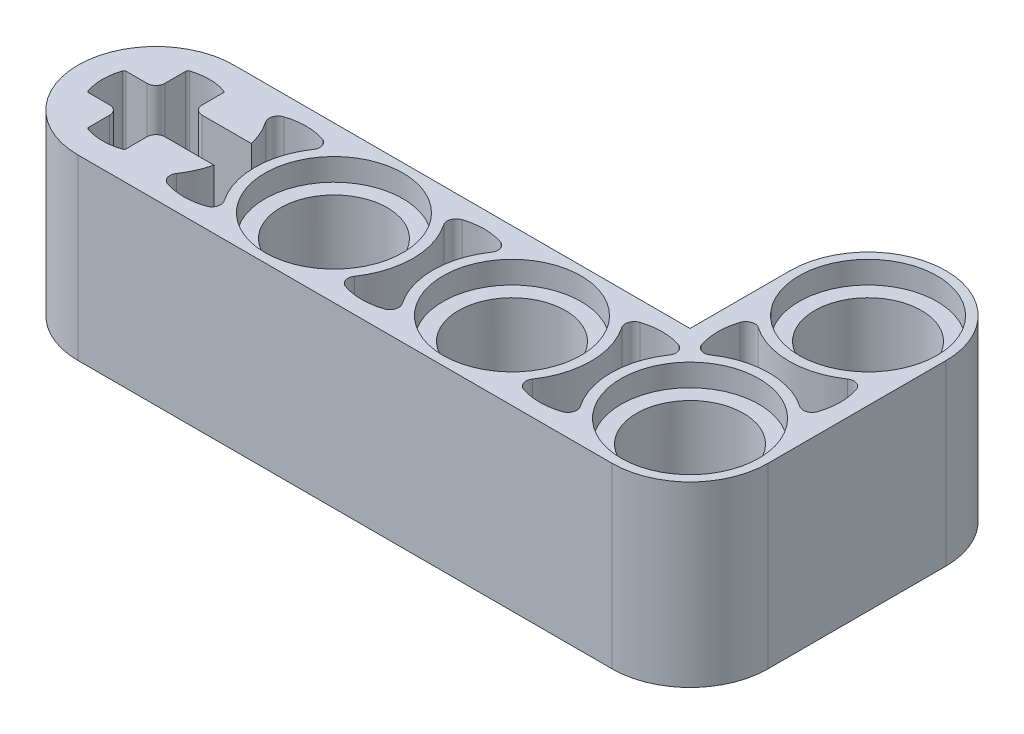
SolidWorks part; units mm, degrees
ref_plane "Front Plane" through (0, 0, 0) normal (0, 0, 1) x (1, 0, 0)
ref_plane "Top Plane" through (0, 0, 0) normal (0, 1, 0) x (1, 0, 0)
ref_plane "Right Plane" through (0, 0, 0) normal (1, 0, 0) x (0, 0, -1)
sketch "Sketch1" plane through (0, 0, 0) normal (0, 1, 0) x (1, 0, 0)
  line L5 (-15.5, -3.5) -> (15.5, -3.5)
  line L6 (-15.5, -3.5) -> (-15.5, 3.5)
  line L11 (-15.5, 3.5) -> (8.5, 3.5)
  line L12 (15.5, -3.5) -> (15.5, 3.5)
  line L13 (-15.5, -3.5) -> (15.5, 3.5) construction
  line L14 (-15.5, 3.5) -> (15.5, -3.5) construction
  line L16 (15.5, 3.5) -> (15.5, 11.5)
  line L17 (15.5, 11.5) -> (8.5, 11.5)
  line L18 (8.5, 3.5) -> (8.5, 11.5)
  point P0 (0, 0)
  dimension "D1" = 31
  dimension "D2" = 7
  dimension "D3" = 7
  dimension "D4" = 8
  dimension "D5" = 24
extrude "Boss-Extrude1" add sketch "Sketch1" along normal blind 8 contours L11 L18 L17 L16 L12 L5 L6
sketch "Sketch3" plane through (0, 8, 0) normal (0, 1, 0) x (1, 0, 0)
  line L0 (-12, 0) -> (-15.5, 0) construction
  line L1 (-15.5, -3.5) -> (-15.5, 3.5) construction
  line L2 (-12, 3.5) -> (-15.5, 3.5)
  line L3 (-15.5, 3.5) -> (-15.5, -3.5)
  line L4 (-15.5, -3.5) -> (-12, -3.5)
  line L5 (12, 0) -> (15.5, 0) construction
  line L6 (15.5, -3.5) -> (15.5, 11.5) construction
  line L7 (12, 0) -> (12, -3.5) construction
  line L8 (15.5, 0) -> (15.5, -3.5)
  line L9 (15.5, -3.5) -> (12, -3.5)
  line L10 (8.5, 3.5) -> (8.5, 11.5) construction
  line L11 (12, 8) -> (12, 11.5) construction
  line L12 (15.5, 11.5) -> (8.5, 11.5) construction
  line L13 (8.5, 8) -> (8.5, 11.5)
  line L14 (8.5, 11.5) -> (15.5, 11.5)
  line L15 (15.5, 11.5) -> (15.5, 8)
  arc A0 (-12, 3.5) -> (-12, -3.5) centre (-12, 0) ccw
  arc A1 (12, -3.5) -> (15.5, 0) centre (12, 0) ccw
  arc A3 (8.5, 8) -> (15.5, 8) centre (12, 8) cw
  line M5 (-15.5, 3.5) -> (-15.5, -3.5)
  line M6 (-15.5, -3.5) -> (15.5, -3.5)
  line M7 (15.5, -3.5) -> (15.5, 11.5)
  line M8 (15.5, 11.5) -> (8.5, 11.5)
  line M9 (8.5, 11.5) -> (8.5, 3.5)
  line M10 (8.5, 3.5) -> (-15.5, 3.5)
  dimension "D1" = 7
  dimension "D6" = 3.5
  dimension "D7" = 3.5
  dimension "D8" = 3.5
  dimension "D2" = 3.5
  dimension "D3" = 3.5
  dimension "D4" = 7
  dimension "D5" = 3.5
extrude "Cut-Extrude1" cut sketch "Sketch3" against normal blind 8 contours A0 M10 M5 | A0 L3 M6 | A1 M6 M7 | A3 M8 M7 | A3 L14 M9
sketch "Sketch8" plane through (0, 8, 0) normal (0, 1, 0) x (1, 0, 0)
  circle A0 centre (12, 8) radius 2.4
  circle A1 centre (12, 0) radius 2.4
  circle A2 centre (4, 0) radius 2.4
  circle A3 centre (-4, 0) radius 2.4
  dimension "D1" = 4.8
  dimension "D4" = 8
  dimension "D5" = 8
  dimension "D2" = 2
  dimension "D3" = 3
extrude "Cut-Extrude4" cut sketch "Sketch8" against normal through all
sketch "Sketch9" plane through (0, 8, 0) normal (0, 1, 0) x (1, 0, 0)
  circle A0 centre (12, 8) radius 3.1
  circle A1 centre (12, 0) radius 3.1
  circle A2 centre (4, 0) radius 3.1
  circle A3 centre (-4, 0) radius 3.1
  dimension "D1" = 6.2
  dimension "D4" = 8
  dimension "D5" = 8
  dimension "D2" = 2
  dimension "D3" = 3
extrude "Cut-Extrude5" cut sketch "Sketch9" against normal blind 1
ref_plane "Plane1" through (0, 4, 0) normal (0, 1, 0) x (1, 0, 0)
mirror "Mirror1" about plane through (0, 4, 0) normal (0, 1, 0) of "Cut-Extrude5"
sketch "Sketch10" plane through (0, 8, 0) normal (0, 1, 0) x (1, 0, 0)
  line L0 (12, 8) -> (12, 0) construction
  arc A0 (9.3899, 4.866) -> (9.3899, 3.134) centre (12, 4) ccw
  arc A1 (9.9954, 2.9299) -> (14.0046, 2.9299) centre (12, 0) cw
  arc A2 (9.9954, 5.0701) -> (14.0046, 5.0701) centre (12, 8) ccw
  arc A3 (14.6101, 3.134) -> (14.6101, 4.866) centre (12, 4) ccw
  arc A4 (14.0046, 2.9299) -> (14.6101, 3.134) centre (14.2304, 3.26) ccw
  arc A5 (14.0046, 5.0701) -> (14.6101, 4.866) centre (14.2304, 4.74) cw
  arc A6 (9.9954, 5.0701) -> (9.3899, 4.866) centre (9.7696, 4.74) ccw
  arc A7 (9.9954, 2.9299) -> (9.3899, 3.134) centre (9.7696, 3.26) cw
  arc A8 (7.134, -2.6101) -> (8.866, -2.6101) centre (8, 0) ccw
  arc A9 (9.0701, -2.0046) -> (8.866, -2.6101) centre (8.74, -2.2304) cw
  arc A10 (6.9299, -2.0046) -> (7.134, -2.6101) centre (7.26, -2.2304) ccw
  arc A11 (9.0701, -2.0046) -> (9.0701, 2.0046) centre (12, 0) cw
  arc A12 (9.0701, 2.0046) -> (8.866, 2.6101) centre (8.74, 2.2304) ccw
  arc A13 (8.866, 2.6101) -> (7.134, 2.6101) centre (8, 0) ccw
  arc A14 (6.9299, 2.0046) -> (7.134, 2.6101) centre (7.26, 2.2304) cw
  arc A15 (6.9299, -2.0046) -> (6.9299, 2.0046) centre (4, 0) ccw
  arc A16 (-0.866, -2.6101) -> (0.866, -2.6101) centre (0, 0) ccw
  arc A17 (1.0701, -2.0046) -> (0.866, -2.6101) centre (0.74, -2.2304) cw
  arc A18 (1.0701, -2.0046) -> (1.0701, 2.0046) centre (4, 0) cw
  arc A19 (1.0701, 2.0046) -> (0.866, 2.6101) centre (0.74, 2.2304) ccw
  arc A20 (0.866, 2.6101) -> (-0.866, 2.6101) centre (0, 0) ccw
  arc A21 (-1.0701, 2.0046) -> (-0.866, 2.6101) centre (-0.74, 2.2304) cw
  arc A22 (-1.0701, -2.0046) -> (-1.0701, 2.0046) centre (-4, 0) ccw
  arc A23 (-1.0701, -2.0046) -> (-0.866, -2.6101) centre (-0.74, -2.2304) ccw
  arc A24 (-8.866, -2.6101) -> (-7.134, -2.6101) centre (-8, 0) ccw
  arc A25 (-6.9299, -2.0046) -> (-7.134, -2.6101) centre (-7.26, -2.2304) cw
  arc A26 (-6.9299, -2.0046) -> (-6.9299, 2.0046) centre (-4, 0) cw
  arc A27 (-6.9299, 2.0046) -> (-7.134, 2.6101) centre (-7.26, 2.2304) ccw
  arc A28 (-7.134, 2.6101) -> (-8.866, 2.6101) centre (-8, 0) ccw
  arc A29 (-9.0701, 2.0046) -> (-8.866, 2.6101) centre (-8.74, 2.2304) cw
  arc A30 (-9.0701, -2.0046) -> (-9.0701, 2.0046) centre (-12, 0) ccw
  arc A31 (-9.0701, -2.0046) -> (-8.866, -2.6101) centre (-8.74, -2.2304) ccw
  point P11 (14.3844, 2.63)
  dimension "D1" = 3.55
  dimension "D2" = 3.55
  dimension "D3" = 2.75
  dimension "D4" = 0.4
  dimension "D7" = 8
  dimension "D8" = 5.6569
  dimension "D6" = 3
  dimension "D5" = 2
extrude "Cut-Extrude6" cut sketch "Sketch10" against normal through all
sketch "Sketch11" plane through (0, 8, 0) normal (0, 1, 0) x (1, 0, 0)
  line L0 (-13.24, 0.84) -> (-14.1777, 0.84)
  line L2 (-12.84, -2.1777) -> (-12.84, -1.24)
  line L4 (-11.16, -2.1777) -> (-11.16, -1.24)
  line L5 (-12.84, -2.2482) -> (-11.16, 2.2482) construction
  line L6 (-12.84, 2.2482) -> (-11.16, -2.2482) construction
  line L7 (-9.8223, 0.84) -> (-10.76, 0.84)
  line L9 (-9.8223, -0.84) -> (-10.76, -0.84)
  line L11 (-9.7518, 0.84) -> (-14.2482, -0.84) construction
  line L12 (-9.7518, -0.84) -> (-14.2482, 0.84) construction
  line L13 (-12.84, 1.24) -> (-12.84, 2.1777)
  line L14 (-11.16, 1.24) -> (-11.16, 2.1777)
  line L15 (-13.24, -0.84) -> (-14.1777, -0.84)
  line L16 (-9.7518, 0.84) -> (-8.5508, 0.84)
  line L17 (-9.7518, -0.84) -> (-8.5508, -0.84)
  line L18 (-9.8223, -0.84) -> (-9.7518, -0.84)
  line L19 (-9.8223, 0.84) -> (-9.7518, 0.84)
  arc A0 (-9.7276, -0.7722) -> (-9.7276, 0.7722) centre (-12, 0) ccw construction
  arc A1 (-11.2278, 2.2724) -> (-12.7722, 2.2724) centre (-12, 0) ccw
  arc A2 (-14.2724, 0.7722) -> (-14.2724, -0.7722) centre (-12, 0) ccw
  arc A3 (-12.7722, -2.2724) -> (-11.2278, -2.2724) centre (-12, 0) ccw
  arc A4 (-12.84, -1.24) -> (-13.24, -0.84) centre (-13.24, -1.24) ccw
  arc A5 (-11.16, -1.24) -> (-10.76, -0.84) centre (-10.76, -1.24) cw
  arc A6 (-10.76, 0.84) -> (-11.16, 1.24) centre (-10.76, 1.24) cw
  arc A7 (-13.24, 0.84) -> (-12.84, 1.24) centre (-13.24, 1.24) ccw
  arc A8 (-14.1777, 0.84) -> (-14.2724, 0.7722) centre (-14.1777, 0.74) ccw
  arc A9 (-14.1777, -0.84) -> (-14.2724, -0.7722) centre (-14.1777, -0.74) cw
  arc A10 (-12.7722, -2.2724) -> (-12.84, -2.1777) centre (-12.74, -2.1777) cw
  arc A11 (-11.2278, -2.2724) -> (-11.16, -2.1777) centre (-11.26, -2.1777) ccw
  arc A12 (-9.7276, -0.7722) -> (-9.8223, -0.84) centre (-9.8223, -0.74) cw construction
  arc A13 (-9.8223, 0.84) -> (-9.7276, 0.7722) centre (-9.8223, 0.74) cw construction
  arc A14 (-11.2278, 2.2724) -> (-11.16, 2.1777) centre (-11.26, 2.1777) cw
  arc A15 (-12.84, 2.1777) -> (-12.7722, 2.2724) centre (-12.74, 2.1777) cw
  arc A16 (-9.0701, -2.0046) -> (-9.0701, 2.0046) centre (-12, 0) ccw construction
  arc A17 (-8.5508, 0.84) -> (-8.5508, -0.84) centre (-12, 0) cw
  point P16 (-12.84, -0.84)
  point P21 (-11.16, 0.84)
  point P24 (-12.84, 0.84)
  dimension "D1" = 4.8
  dimension "D4" = 0.4
  dimension "D5" = 0.1
  dimension "D2" = 1.68
  dimension "D3" = 1.68
extrude "Cut-Extrude7" cut sketch "Sketch11" against normal through all
